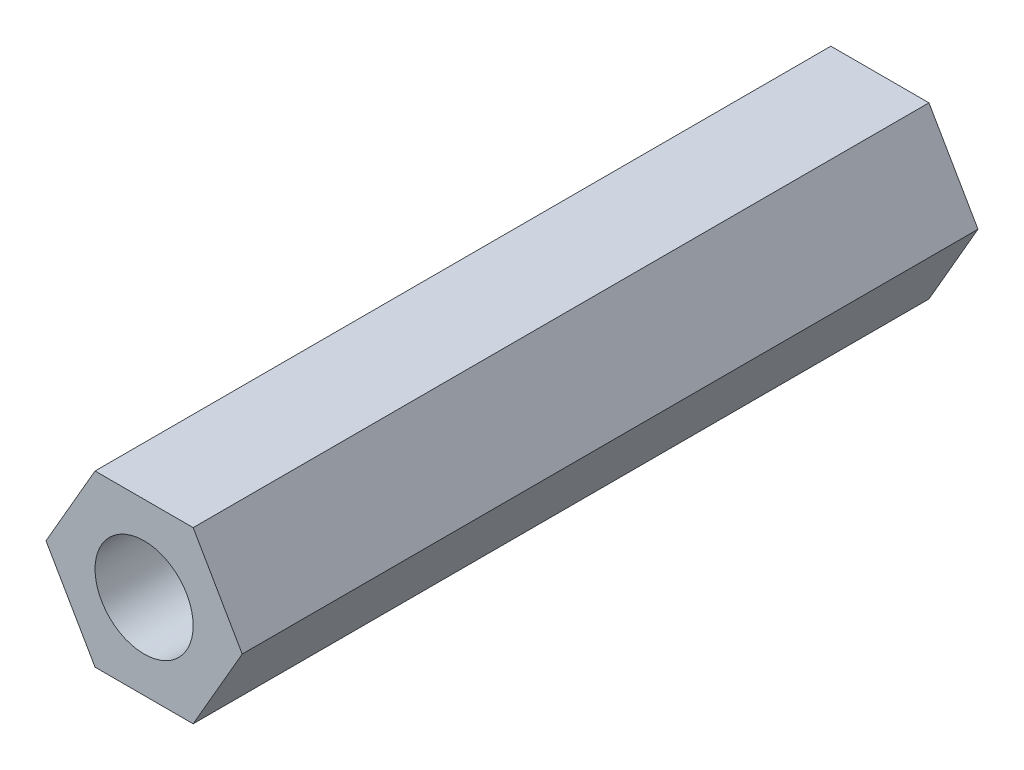
SolidWorks part; units mm, degrees
material "黄铜"
ref_plane "前视基准面" through (0, 0, 0) normal (0, 0, 1) x (1, 0, 0)
ref_plane "上视基准面" through (0, 0, 0) normal (0, 1, 0) x (1, 0, 0)
ref_plane "右视基准面" through (0, 0, 0) normal (1, 0, 0) x (0, 0, -1)
other "Configuration Table"
sketch "草图1" plane through (0, 0, 0) normal (0, 0, 1) x (1, 0, 0)
  line L1 (-2, 3.4641) -> (-4, 0)
  line L2 (-4, 0) -> (-2, -3.4641)
  line L3 (-2, -3.4641) -> (2, -3.4641)
  line L4 (2, -3.4641) -> (4, 0)
  line L5 (4, 0) -> (2, 3.4641)
  line L6 (2, 3.4641) -> (-2, 3.4641)
  circle A0 centre (0, 0) radius 3.4641 construction
  circle A1 centre (0, 0) radius 2
  dimension "D1" = 4
  dimension "D2" = 4
extrude "凸台-拉伸1" add sketch "草图1" along normal blind 30
